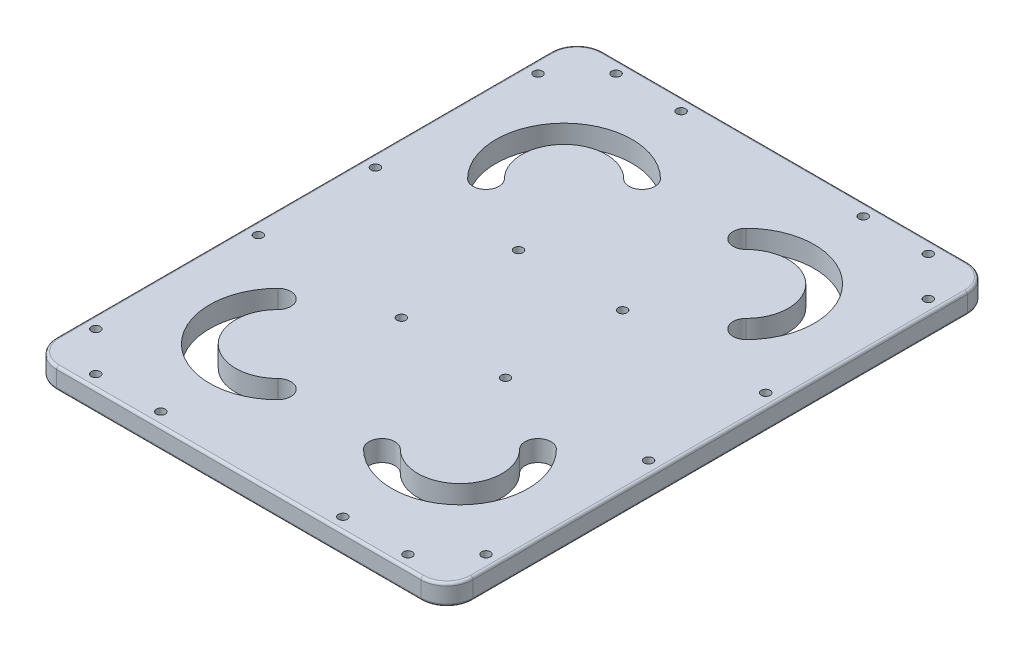
SolidWorks part; units mm, degrees
ref_plane "Front Plane" through (0, 0, 0) normal (0, 0, 1) x (1, 0, 0)
ref_plane "Top Plane" through (0, 0, 0) normal (0, 1, 0) x (1, 0, 0)
ref_plane "Right Plane" through (0, 0, 0) normal (1, 0, 0) x (0, 0, -1)
sketch "Sketch1" plane through (0, 0, 0) normal (0, 1, 0) x (1, 0, 0)
  line L1 (-80, 105) -> (80, 105)
  line L2 (-80, 105) -> (-80, -105)
  line L3 (-80, -105) -> (80, -105)
  line L4 (80, 105) -> (80, -105)
  line L5 (-80, 105) -> (80, -105) construction
  line L6 (-80, -105) -> (80, 105) construction
  point P0 (0, 0)
  dimension "D1" = 160
  dimension "D2" = 210
extrude "Boss-Extrude1" add sketch "Sketch1" along normal blind 8
sketch "Sketch2" plane through (0, 8, 0) normal (0, 1, 0) x (1, 0, 0)
  line L0 (0, 105) -> (0, -105) construction
  line L1 (80, 105) -> (-80, 105) construction
  line L2 (-80, -105) -> (80, -105) construction
  line L3 (-80, 0) -> (80, 0) construction
  line L4 (-80, 105) -> (-80, -105) construction
  line L5 (80, -105) -> (80, 105) construction
  line L6 (-75, 27.5) -> (-75, -27.5) construction
  line L7 (-70, 27.5) -> (-80, 27.5)
  line L8 (-70, 27.5) -> (-70, -27.5)
  line L9 (-70, -27.5) -> (-80, -27.5)
  line L10 (-80, 27.5) -> (-80, -27.5)
  line L11 (-70, 27.5) -> (-80, -27.5) construction
  line L12 (-70, -27.5) -> (-80, 27.5) construction
  line L13 (75, 27.5) -> (75, -27.5) construction
  line L14 (70, 27.5) -> (80, 27.5)
  line L15 (70, 27.5) -> (70, -27.5)
  line L16 (70, -27.5) -> (80, -27.5)
  line L17 (80, 27.5) -> (80, -27.5)
  line L18 (70, 27.5) -> (80, -27.5) construction
  line L19 (70, -27.5) -> (80, 27.5) construction
  circle A0 centre (-75, 22.5) radius 1.7
  circle A1 centre (-75, -22.5) radius 1.7
  circle A2 centre (75, 22.5) radius 1.7
  circle A3 centre (75, -22.5) radius 1.7
  point P12 (-75, 0)
  point P23 (75, 0)
  dimension "D3" = 3.4
  dimension "D4" = 3.4
  dimension "D5" = 5
  dimension "D6" = 5
  dimension "D9" = 3.4
  dimension "D10" = 3.4
  dimension "D11" = 5
  dimension "D12" = 5
  dimension "D1" = 10
  dimension "D2" = 55
  dimension "D7" = 10
  dimension "D8" = 55
extrude "Cut-Extrude1" cut sketch "Sketch2" against normal blind 37 contours A1 | A0 | A3 | A2
fillet "Fillet1" radius 10 4 edges at (-80, 4, 105) (80, 4, 105) (80, 4, -105) (-80, 4, -105)
sketch "Sketch3" plane through (0, 8, 0) normal (0, 1, 0) x (1, 0, 0)
  line L0 (0, 105) -> (0, -105) construction
  line L1 (70, 105) -> (-70, 105) construction
  line L2 (-70, -105) -> (70, -105) construction
  line L3 (-80, 0) -> (80, 0) construction
  line L4 (-80, 95) -> (-80, -95) construction
  line L5 (80, -95) -> (80, 95) construction
  line L6 (-20, 27.5) -> (-20, -27.5) construction
  line L7 (15, 27.5) -> (25, 27.5)
  line L8 (15, 27.5) -> (15, -27.5)
  line L9 (15, -27.5) -> (25, -27.5)
  line L10 (25, 27.5) -> (25, -27.5)
  line L11 (15, 27.5) -> (25, -27.5) construction
  line L12 (15, -27.5) -> (25, 27.5) construction
  line L13 (-25, 27.5) -> (-15, 27.5)
  line L14 (-25, 27.5) -> (-25, -27.5)
  line L15 (-25, -27.5) -> (-15, -27.5)
  line L16 (-15, 27.5) -> (-15, -27.5)
  line L17 (-25, 27.5) -> (-15, -27.5) construction
  line L18 (-25, -27.5) -> (-15, 27.5) construction
  line L19 (20, 27.5) -> (20, -27.5) construction
  circle A0 centre (-20, 22.5) radius 1.7
  circle A1 centre (-20, -22.5) radius 1.7
  circle A2 centre (20, -22.5) radius 1.7
  circle A3 centre (20, 22.5) radius 1.7
  point P12 (20, 0)
  point P17 (-20, 0)
  dimension "D7" = 3.4
  dimension "D8" = 3.4
  dimension "D9" = 3.4
  dimension "D10" = 3.4
  dimension "D11" = 5
  dimension "D12" = 5
  dimension "D13" = 5
  dimension "D14" = 5
  dimension "D1" = 15
  dimension "D2" = 15
  dimension "D3" = 10
  dimension "D4" = 10
  dimension "D5" = 55
  dimension "D6" = 55
extrude "Cut-Extrude2" cut sketch "Sketch3" against normal blind 480 contours A0 | A1 | A2 | A3
sketch "Sketch4" plane through (0, 8, 0) normal (0, 1, 0) x (1, 0, 0)
  line L0 (0, 105) -> (0, -105) construction
  line L1 (70, 105) -> (-70, 105) construction
  line L2 (-70, -105) -> (70, -105) construction
  line L3 (-80, 0) -> (80, 0) construction
  line L4 (-80, 95) -> (-80, -95) construction
  line L5 (80, -95) -> (80, 95) construction
  line L6 (70.0117, -85) -> (80, -85) construction
  line L7 (70.0117, -95) -> (80, -95)
  line L8 (70.0117, -95) -> (70.0117, -80)
  line L9 (70.0117, -80) -> (80, -80)
  line L10 (80, -95) -> (80, -80)
  line L11 (70.0117, -95) -> (55.0117, -95)
  line L12 (70.0117, -95) -> (70.0117, -105)
  line L13 (70.0117, -105) -> (55.0117, -105)
  line L14 (55.0117, -95) -> (55.0117, -105)
  line L15 (60.0117, -95) -> (60.0117, -105) construction
  line L16 (55.0117, -105) -> (70.0117, -105)
  line L17 (-60.0117, -95) -> (-60.0117, -105) construction
  line L18 (-70.0117, -85) -> (-80, -85) construction
  line L19 (-55.0117, -105) -> (-70.0117, -105)
  line L20 (-55.0117, -95) -> (-55.0117, -105)
  line L21 (-70.0117, -105) -> (-55.0117, -105)
  line L22 (-70.0117, -95) -> (-70.0117, -105)
  line L23 (-70.0117, -95) -> (-55.0117, -95)
  line L24 (-80, -95) -> (-80, -80)
  line L25 (-70.0117, -80) -> (-80, -80)
  line L26 (-70.0117, -95) -> (-70.0117, -80)
  line L27 (-70.0117, -95) -> (-80, -95)
  line L28 (-70.0117, 85) -> (-80, 85) construction
  line L29 (-60.0117, 95) -> (-60.0117, 105) construction
  line L30 (60.0117, 95) -> (60.0117, 105) construction
  line L31 (70.0117, 85) -> (80, 85) construction
  line L32 (-70.0117, 95) -> (-80, 95)
  line L33 (-70.0117, 95) -> (-70.0117, 80)
  line L34 (-70.0117, 80) -> (-80, 80)
  line L35 (-80, 95) -> (-80, 80)
  line L36 (-70.0117, 95) -> (-55.0117, 95)
  line L37 (-70.0117, 95) -> (-70.0117, 105)
  line L38 (-70.0117, 105) -> (-55.0117, 105)
  line L39 (-55.0117, 95) -> (-55.0117, 105)
  line L40 (-55.0117, 105) -> (-70.0117, 105)
  line L41 (55.0117, 105) -> (70.0117, 105)
  line L42 (55.0117, 95) -> (55.0117, 105)
  line L43 (70.0117, 105) -> (55.0117, 105)
  line L44 (70.0117, 95) -> (70.0117, 105)
  line L45 (70.0117, 95) -> (55.0117, 95)
  line L46 (80, 95) -> (80, 80)
  line L47 (70.0117, 80) -> (80, 80)
  line L48 (70.0117, 95) -> (70.0117, 80)
  line L49 (70.0117, 95) -> (80, 95)
  arc A0 (70.0117, -105) -> (80.0117, -95) centre (70.0117, -95) ccw
  circle A1 centre (75.0059, -85) radius 1.7
  circle A2 centre (60.0117, -100) radius 1.7
  circle A3 centre (-60.0117, -100) radius 1.7
  circle A4 centre (-75.0059, -85) radius 1.7
  arc A5 (-70.0117, -105) -> (-80.0117, -95) centre (-70.0117, -95) cw
  arc A6 (-70.0117, 105) -> (-80.0117, 95) centre (-70.0117, 95) ccw
  circle A7 centre (-75.0059, 85) radius 1.7
  circle A8 centre (-60.0117, 100) radius 1.7
  circle A9 centre (60.0117, 100) radius 1.7
  circle A10 centre (75.0059, 85) radius 1.7
  arc A11 (70.0117, 105) -> (80.0117, 95) centre (70.0117, 95) cw
  dimension "D3" = 5
  dimension "D5" = 3.4
  dimension "D6" = 3.4
  dimension "D1" = 15
  dimension "D2" = 15
  dimension "D4" = 5
extrude "Cut-Extrude3" cut sketch "Sketch4" against normal blind 480 contours A7 | A8 | A4 | A3 | A2 | A1 | A10 | A9
sketch "Sketch5" plane through (0, 8, 0) normal (0, 1, 0) x (1, 0, 0)
  line L0 (0, 105) -> (0, -105) construction
  line L1 (70, 105) -> (-70, 105) construction
  line L2 (-70, -105) -> (70, -105) construction
  line L3 (-80, 100) -> (80, 100) construction
  line L4 (-80, 95) -> (-80, -95) construction
  line L5 (80, -95) -> (80, 95) construction
  line L6 (-80, -100) -> (80, -100) construction
  circle A0 centre (35, -100) radius 1.7
  circle A1 centre (-35, -100) radius 1.7
  circle A2 centre (35, 100) radius 1.7
  circle A3 centre (-35, 100) radius 1.7
  dimension "D1" = 3.4
  dimension "D2" = 3.4
  dimension "D3" = 35
  dimension "D4" = 35
  dimension "D5" = 3.4
  dimension "D6" = 3.4
  dimension "D7" = 35
  dimension "D8" = 35
  dimension "D9" = 5
  dimension "D10" = 5
extrude "Cut-Extrude4" cut sketch "Sketch5" against normal blind 480
fillet "Fillet2" radius 1 16 edges at (-77.0711, 0, -102.0711) (0, 0, -105) (77.0711, 0, -102.0711) (80, 0, 0) (77.0711, 0, 102.0711) (0, 0, 105) (-77.0711, 0, 102.0711) (-77.0711, 8, -102.0711) (0, 8, -105) (77.0711, 8, -102.0711) (80, 8, 0) (77.0711, 8, 102.0711) (0, 8, 105) (-77.0711, 8, 102.0711) (-80, 0, 0) (-80, 8, 0)
sketch "Sketch6" plane through (0, 8, 0) normal (0, 1, 0) x (1, 0, 0)
  line L0 (0, 105) -> (0, -105) construction
  line L1 (-70, 105) -> (70, 105) construction
  line L2 (70, -105) -> (-70, -105) construction
  line L3 (-80, 0) -> (80, 0) construction
  line L4 (-80, -95) -> (-80, 95) construction
  line L5 (80, 95) -> (80, -95) construction
  line L6 (0, 70) -> (20, 70) construction
  line L7 (50, 0) -> (50, 40) construction
  arc A0 (20, 70) -> (50, 40) centre (35, 55) cw construction
  arc A1 (53.5355, 36.4645) -> (16.4645, 73.5355) centre (35, 55) ccw
  arc A2 (46.4645, 43.5355) -> (23.5355, 66.4645) centre (35, 55) ccw
  arc A3 (46.4645, 43.5355) -> (53.5355, 36.4645) centre (50, 40) ccw
  arc A4 (16.4645, 73.5355) -> (23.5355, 66.4645) centre (20, 70) ccw
  arc A5 (-20, 70) -> (-50, 40) centre (-35, 55) ccw construction
  arc A6 (-53.5355, 36.4645) -> (-16.4645, 73.5355) centre (-35, 55) cw
  arc A7 (-46.4645, 43.5355) -> (-23.5355, 66.4645) centre (-35, 55) cw
  arc A8 (-46.4645, 43.5355) -> (-53.5355, 36.4645) centre (-50, 40) cw
  arc A9 (-16.4645, 73.5355) -> (-23.5355, 66.4645) centre (-20, 70) cw
  arc A10 (20, -70) -> (50, -40) centre (35, -55) ccw construction
  arc A11 (53.5355, -36.4645) -> (16.4645, -73.5355) centre (35, -55) cw
  arc A12 (46.4645, -43.5355) -> (23.5355, -66.4645) centre (35, -55) cw
  arc A13 (46.4645, -43.5355) -> (53.5355, -36.4645) centre (50, -40) cw
  arc A14 (16.4645, -73.5355) -> (23.5355, -66.4645) centre (20, -70) cw
  arc A15 (-20, -70) -> (-50, -40) centre (-35, -55) cw construction
  arc A16 (-53.5355, -36.4645) -> (-16.4645, -73.5355) centre (-35, -55) ccw
  arc A17 (-46.4645, -43.5355) -> (-23.5355, -66.4645) centre (-35, -55) ccw
  arc A18 (-46.4645, -43.5355) -> (-53.5355, -36.4645) centre (-50, -40) ccw
  arc A19 (-16.4645, -73.5355) -> (-23.5355, -66.4645) centre (-20, -70) ccw
  point P17 (50, 70)
  point P25 (-50, 70)
  point P33 (50, -70)
  point P41 (-50, -70)
  dimension "D5" = 10
  dimension "D1" = 70
  dimension "D2" = 50
  dimension "D3" = 40
  dimension "D4" = 20
extrude "Cut-Extrude5" cut sketch "Sketch6" against normal blind 63
